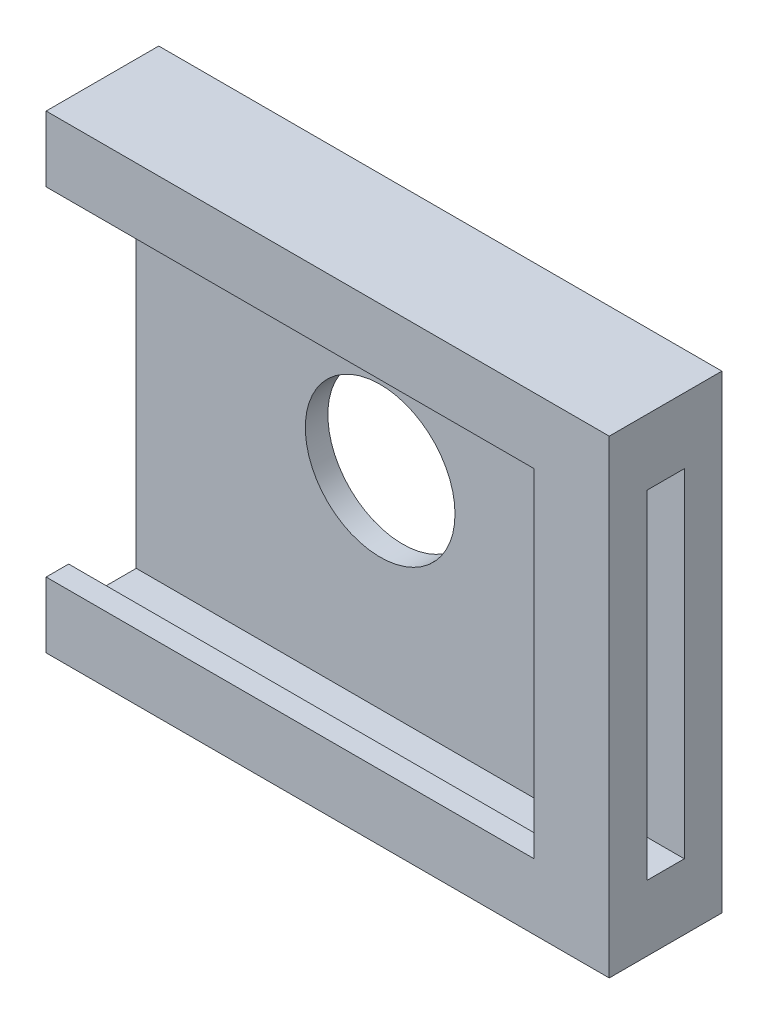
SolidWorks part; units mm, degrees
ref_plane "Front Plane" through (0, 0, 0) normal (0, 0, 1) x (1, 0, 0)
ref_plane "Top Plane" through (0, 0, 0) normal (0, 1, 0) x (1, 0, 0)
ref_plane "Right Plane" through (0, 0, 0) normal (1, 0, 0) x (0, 0, -1)
sketch "Sketch1" plane through (0, 0, 0) normal (0, 0, 1) x (1, 0, 0)
  line L1 (0, 0) -> (-15, 0)
  line L2 (0, 0) -> (0, 12.5)
  line L3 (0, 12.5) -> (-15, 12.5)
  line L4 (-15, 0) -> (-15, 12.5)
  line L5 (0, 0) -> (-15, 12.5) construction
  line L6 (0, 12.5) -> (-15, 0) construction
  point P4 (-7.5, 6.25)
  dimension "D1" = 12.5
  dimension "D2" = 15
extrude "Boss-Extrude1" add sketch "Sketch1" along normal blind 3
sketch "Sketch3" plane through (-15, 0, 0) normal (-1, 0, 0) x (0, 0, 1)
  line L0 (3, 12.5) -> (3, 0) construction
  line L1 (0.6, 11.75) -> (2.4, 11.75)
  line L2 (0.6, 11.75) -> (0.6, 0.75)
  line L3 (0.6, 0.75) -> (2.4, 0.75)
  line L4 (2.4, 11.75) -> (2.4, 10.75)
  line L5 (0.6, 11.75) -> (2.4, 0.75) construction
  line L6 (0.6, 0.75) -> (2.4, 11.75) construction
  line L7 (2.4, 1.75) -> (3, 1.75)
  line L9 (2.4, 10.75) -> (3, 10.75)
  line L10 (3, 1.75) -> (3, 10.75)
  line L11 (2.4, 1.75) -> (3, 10.75) construction
  line L12 (2.4, 10.75) -> (3, 1.75) construction
  line L13 (2.4, 1.75) -> (2.4, 0.75)
  line L14 (3, 12.5) -> (0, 12.5) construction
  line L15 (0.6, 11.75) -> (0.6, 12.5) construction
  line L16 (0.6, 0.75) -> (0.6, 0) construction
  line L17 (3, 0) -> (0, 0) construction
  line L18 (0.6, 11.75) -> (0, 11.75) construction
  line L19 (0, 12.5) -> (0, 0) construction
  point P4 (1.5, 6.25)
  point P9 (2.7, 6.25)
  dimension "D1" = 11
  dimension "D2" = 1.8
  dimension "D3" = 9
extrude "Cut-Extrude1" cut sketch "Sketch3" against normal offset from surface (13 mm away) 2 up to face at (0, 6.25, 1.5)
sketch "Sketch4" plane through (-2, 0, 0) normal (-1, 0, 0) x (0, 0, 1)
  line L0 (2, 10.75) -> (2.4, 10.75) construction
  line L1 (1, 10.75) -> (2, 10.75)
  line L2 (1, 10.75) -> (1, 1.75)
  line L3 (1, 1.75) -> (2, 1.75)
  line L4 (2, 10.75) -> (2, 1.75)
  line L5 (1, 10.75) -> (2, 1.75) construction
  line L6 (1, 1.75) -> (2, 10.75) construction
  line L7 (1, 10.75) -> (1, 11.75) construction
  line L8 (1, 10.75) -> (0.6, 10.75) construction
  line L9 (0.6, 11.75) -> (0.6, 0.75) construction
  line L10 (2.4, 11.75) -> (0.6, 11.75) construction
  line L11 (1, 1.75) -> (1, 0.75) construction
  line L12 (0.6, 0.75) -> (2.4, 0.75) construction
  line L13 (2.4, 10.75) -> (2.4, 11.75) construction
  point P4 (1.5, 6.25)
  point P5 (2.4, 10.9245)
  dimension "D1" = 1
  dimension "D2" = 9
extrude "Cut-Extrude2" cut sketch "Sketch4" against normal through all
extrude "Cut-Extrude3" cut sketch "Sketch5" against normal through all
sketch "Sketch5" plane through (-632.3963, -864.5729, 0.6) normal (0, 0, 1) x (1, 0, 0)
  circle A0 centre (623.8939, 870.8229) radius 1.9939
